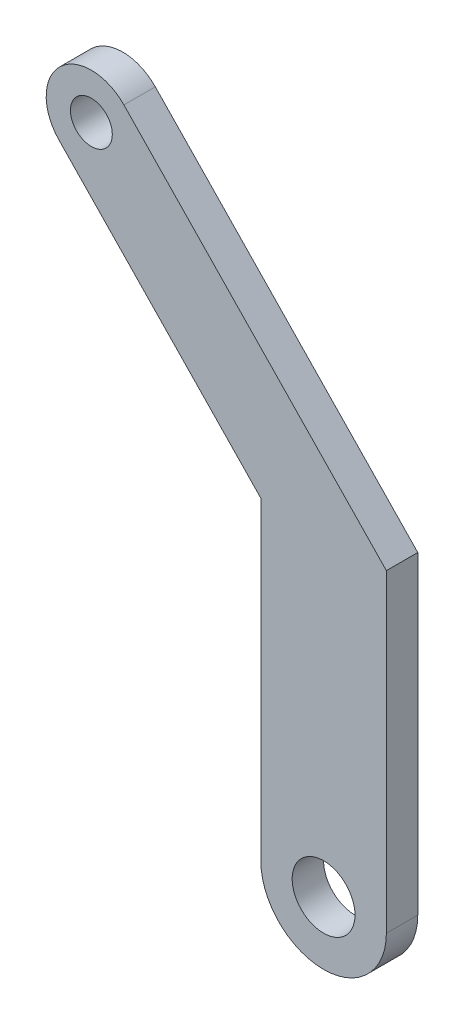
SolidWorks part; units mm, degrees
material "黄铜"
ref_plane "前视基准面" through (0, 0, 0) normal (0, 0, 1) x (1, 0, 0)
ref_plane "上视基准面" through (0, 0, 0) normal (0, 1, 0) x (1, 0, 0)
ref_plane "右视基准面" through (0, 0, 0) normal (1, 0, 0) x (0, 0, -1)
sketch "草图1" plane through (0, 0, 0) normal (0, 0, 1) x (1, 0, 0)
  line L0 (-13.3723, 0) -> (-13.3723, 150)
  line L1 (46.6277, 0) -> (46.6277, 150)
  line L2 (-13.3723, 150) -> (-109.8418, 250)
  line L3 (46.6277, 150) -> (-78.7639, 279.9806)
  arc A0 (-13.3723, 0) -> (46.6277, 0) centre (16.6277, 0) ccw
  arc A1 (-78.7639, 279.9806) -> (-109.8418, 250) centre (-94.3028, 264.9903) ccw
  circle A2 centre (16.6277, 0) radius 15
  circle A3 centre (-94.3028, 264.9903) radius 10
  dimension "D1" = 60
  dimension "D2" = 150
  dimension "D3" = 150
  dimension "D4" = 250
extrude "凸台-拉伸1" add sketch "草图1" along normal blind 15
